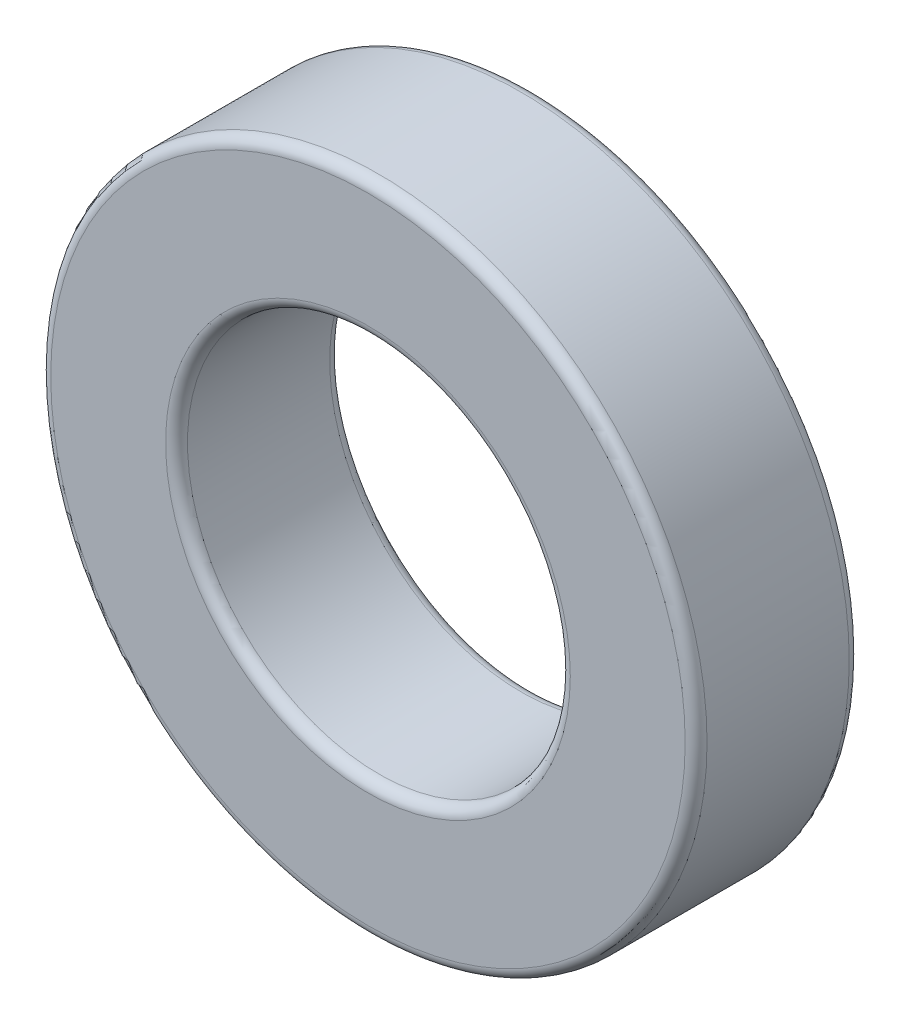
SolidWorks part; units mm, degrees
ref_plane "Front Plane" through (0, 0, 0) normal (0, 0, 1) x (1, 0, 0)
ref_plane "Top Plane" through (0, 0, 0) normal (0, 1, 0) x (1, 0, 0)
ref_plane "Right Plane" through (0, 0, 0) normal (1, 0, 0) x (0, 0, -1)
sketch "Sketch1" plane through (0, 0, 0) normal (0, 0, 1) x (1, 0, 0)
  circle A0 centre (0, 0) radius 1.5
  circle A1 centre (0, 0) radius 0.875
  dimension "D1" = 3
  dimension "D2" = 1.75
extrude "Boss-Extrude1" add sketch "Sketch1" along normal blind 0.75
fillet "Fillet1" radius 0.05 4 edges at (0.875, 0, 0) (1.5, 0, 0) (0.875, 0, 0.75) (1.5, 0, 0.75)
